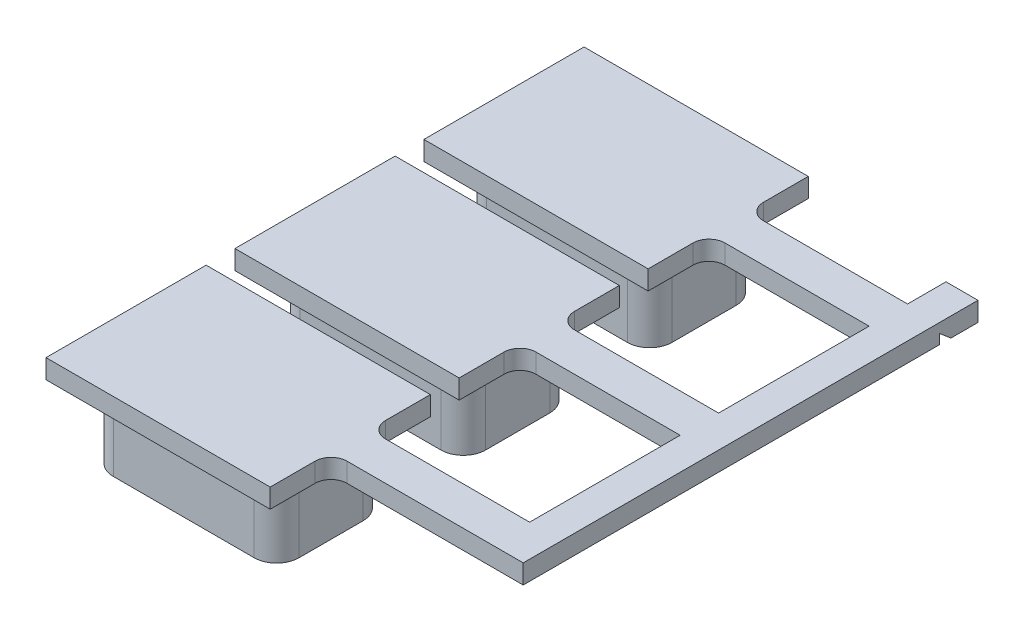
SolidWorks part; units mm, degrees
ref_plane "前视基准面" through (0, 0, 0) normal (0, 0, 1) x (1, 0, 0)
ref_plane "上视基准面" through (0, 0, 0) normal (0, 1, 0) x (1, 0, 0)
ref_plane "右视基准面" through (0, 0, 0) normal (1, 0, 0) x (0, 0, -1)
sketch "草图1" plane through (0, 0, 0) normal (0, 1, 0) x (1, 0, 0)
  line L0 (-2.2, 1.7) -> (2.2, 1.7)
  line L5 (-2.2, 7.5287) -> (2.2, 7.5287)
  line L6 (2.9, 6.8287) -> (2.9, 4.8287)
  line L7 (2.9, 1) -> (2.9, -1)
  line L8 (-2.2, -1.7) -> (2.2, -1.7)
  line L9 (-2.9, 1) -> (-2.9, -1)
  line L10 (-2.2, 4.1287) -> (2.2, 4.1287)
  line L11 (-2.9, 6.8287) -> (-2.9, 4.8287)
  line L12 (-2.2, 13.3491) -> (2.2, 13.3491)
  line L13 (2.9, 12.6491) -> (2.9, 10.6491)
  line L14 (-2.2, 9.9491) -> (2.2, 9.9491)
  line L15 (-2.9, 12.6491) -> (-2.9, 10.6491)
  arc A4 (2.2, 1.7) -> (2.9, 1) centre (2.2, 1) cw
  arc A5 (2.2, -1.7) -> (2.9, -1) centre (2.2, -1) ccw
  arc A6 (-2.9, -1) -> (-2.2, -1.7) centre (-2.2, -1) ccw
  arc A7 (-2.2, 1.7) -> (-2.9, 1) centre (-2.2, 1) ccw
  arc A8 (2.2, 7.5287) -> (2.9, 6.8287) centre (2.2, 6.8287) cw
  arc A9 (2.2, 4.1287) -> (2.9, 4.8287) centre (2.2, 4.8287) ccw
  arc A10 (-2.9, 4.8287) -> (-2.2, 4.1287) centre (-2.2, 4.8287) ccw
  arc A11 (-2.2, 7.5287) -> (-2.9, 6.8287) centre (-2.2, 6.8287) ccw
  arc A12 (2.2, 13.3491) -> (2.9, 12.6491) centre (2.2, 12.6491) cw
  arc A13 (2.2, 9.9491) -> (2.9, 10.6491) centre (2.2, 10.6491) ccw
  arc A14 (-2.9, 10.6491) -> (-2.2, 9.9491) centre (-2.2, 10.6491) ccw
  arc A15 (-2.2, 13.3491) -> (-2.9, 12.6491) centre (-2.2, 12.6491) ccw
  point P0 (0, 0)
  point P1 (-0.0497, 5.8287)
  point P15 (-0.0145, 11.6491)
  point P40 (0, 0)
  point P41 (0, 0)
  point P42 (0, 0)
  point P43 (0, 0)
  point P44 (0, 0)
  dimension "D1" = 3.4
  dimension "D2" = 5.8
extrude "凸台-拉伸1" add sketch "草图1" along normal blind 3
sketch "草图2" plane through (0, 3, 0) normal (0, 1, 0) x (1, 0, 0)
  line L1 (-3.4633, 14.2631) -> (3.5367, 14.2631)
  line L2 (-3.4633, 14.2631) -> (-3.4633, 9.2631)
  line L3 (-3.4633, 9.2631) -> (3.5367, 9.2631)
  line L4 (3.5367, 14.2631) -> (3.5367, 9.2631)
  line L5 (-3.4633, 8.3631) -> (3.5367, 8.3631)
  line L6 (-3.4633, 8.3631) -> (-3.4633, 3.3631)
  line L7 (-3.4633, 3.3631) -> (3.5367, 3.3631)
  line L8 (3.5367, 8.3631) -> (3.5367, 3.3631)
  line L9 (3.5367, 2.4631) -> (-3.4633, 2.4631)
  line L10 (3.5367, 2.4631) -> (3.5367, -2.5369)
  line L11 (3.5367, -2.5369) -> (-3.4633, -2.5369)
  line L12 (-3.4633, 2.4631) -> (-3.4633, -2.5369)
  point P12 (0, 0)
  point P13 (0, 0)
  point P14 (-3.2061, 13.7487)
  point P15 (0, 0)
  point P16 (0, 0)
  point P17 (-3.7633, 14.3917)
  point P18 (0, 0)
  point P19 (0, 0)
  point P20 (0.6515, 17.6921)
  point P21 (-3.4633, 14.2631)
  point P22 (0, 0)
  dimension "D1" = 5
  dimension "D2" = 5
  dimension "D3" = 5
  dimension "D4" = 7
  dimension "D5" = 0.9
  dimension "D6" = 0.9
extrude "凸台-拉伸2" add sketch "草图2" against normal blind 0.6
sketch "草图3" plane through (0, 3, 0) normal (0, 1, 0) x (1, 0, 0)
  line L0 (3.5367, 9.2631) -> (3.5367, 14.2631) construction
  line L1 (3.5367, 12.3631) -> (9.5367, 12.3631)
  line L2 (3.5367, 12.3631) -> (3.5367, 11.1631)
  line L3 (3.5367, 11.1631) -> (9.5367, 11.1631)
  line L4 (9.5367, 12.3631) -> (9.5367, 11.1631)
  line L5 (3.5367, 3.3631) -> (3.5367, 8.3631) construction
  line L6 (3.5367, 6.4631) -> (9.5367, 6.4631)
  line L7 (3.5367, 6.4631) -> (3.5367, 5.2631)
  line L8 (3.5367, 5.2631) -> (9.5367, 5.2631)
  line L9 (9.5367, 6.4631) -> (9.5367, 5.2631)
  line L10 (3.5367, -2.5369) -> (3.5367, 2.4631) construction
  line L11 (3.5367, 0.5631) -> (9.5367, 0.5631)
  line L12 (3.5367, 0.5631) -> (3.5367, -0.6369)
  line L13 (3.5367, -0.6369) -> (9.5367, -0.6369)
  line L14 (9.5367, 0.5631) -> (9.5367, -0.6369)
  line L15 (-3.4633, 14.2631) -> (-3.4633, 9.2631) construction
  line L16 (-3.4633, 8.3631) -> (-3.4633, 3.3631) construction
  line L17 (-3.4633, 2.4631) -> (-3.4633, -2.5369) construction
  point P20 (-3.4633, 11.7631)
  point P21 (9.5367, 11.7631)
  point P24 (-3.4633, 5.8631)
  point P25 (9.5367, 5.8631)
  point P28 (-3.4633, -0.0369)
  point P29 (9.5367, -0.0369)
  dimension "D3" = 1.2
  dimension "D4" = 6
extrude "凸台-拉伸3" add sketch "草图3" against normal blind 0.6
sketch "草图4" plane through (0, 2.4, 0) normal (0, -1, 0) x (1, 0, 0)
  line L0 (3.5367, 0.6369) -> (9.5367, 0.6369) construction
  line L1 (9.5367, 0.6369) -> (8.5367, 0.6369)
  line L2 (9.5367, 0.6369) -> (9.5367, -12.3631)
  line L3 (9.5367, -12.3631) -> (8.5367, -12.3631)
  line L4 (8.5367, 0.6369) -> (8.5367, -12.3631)
  line L5 (9.5367, -12.3631) -> (3.5367, -12.3631) construction
  point P8 (0, 0)
  point P9 (0, 0)
  point P10 (7.9786, -5.2631)
  dimension "D1" = 1
extrude "凸台-拉伸4" add sketch "草图4" against normal blind 0.6
fillet "圆角1" radius 0.5 6 edges at (3.5367, 2.7, -12.3631) (3.5367, 2.7, -11.1631) (3.5367, 2.7, -5.2631) (3.5367, 2.7, -6.4631) (3.5367, 2.7, 0.6369) (3.5367, 2.7, -0.5631)
sketch "草图5" plane through (0, 0, -12.3631) normal (0, 0, -1) x (-1, 0, 0)
  line L0 (-4.0367, 3) -> (-9.5367, 3) construction
  line L1 (-9.5367, 2.4) -> (-8.5367, 2.4)
  line L2 (-9.5367, 2.4) -> (-9.5367, 3)
  line L3 (-9.5367, 3) -> (-8.5367, 3)
  line L4 (-8.5367, 2.4) -> (-8.5367, 3)
  point P7 (0, 0)
  point P8 (0, 0)
  point P9 (0, 0)
  dimension "D1" = 1
  dimension "D2" = 0.6
extrude "凸台-拉伸5" add sketch "草图5" along normal blind 1.2
sketch "草图6" plane through (8.5367, 0, 0) normal (-1, 0, 0) x (0, 0, 1)
  line L0 (-12.3631, 2.4) -> (-12.3631, 2.7)
  line L1 (-12.3631, 2.4) -> (-12.3631, 3) construction
  line L2 (-12.3631, 2.7) -> (-12.7202, 2.4)
  line L3 (-13.5631, 2.4) -> (-12.3631, 2.4) construction
  line L4 (-12.7202, 2.4) -> (-12.3631, 2.4)
extrude "切除-拉伸1" cut sketch "草图6" against normal blind 1
